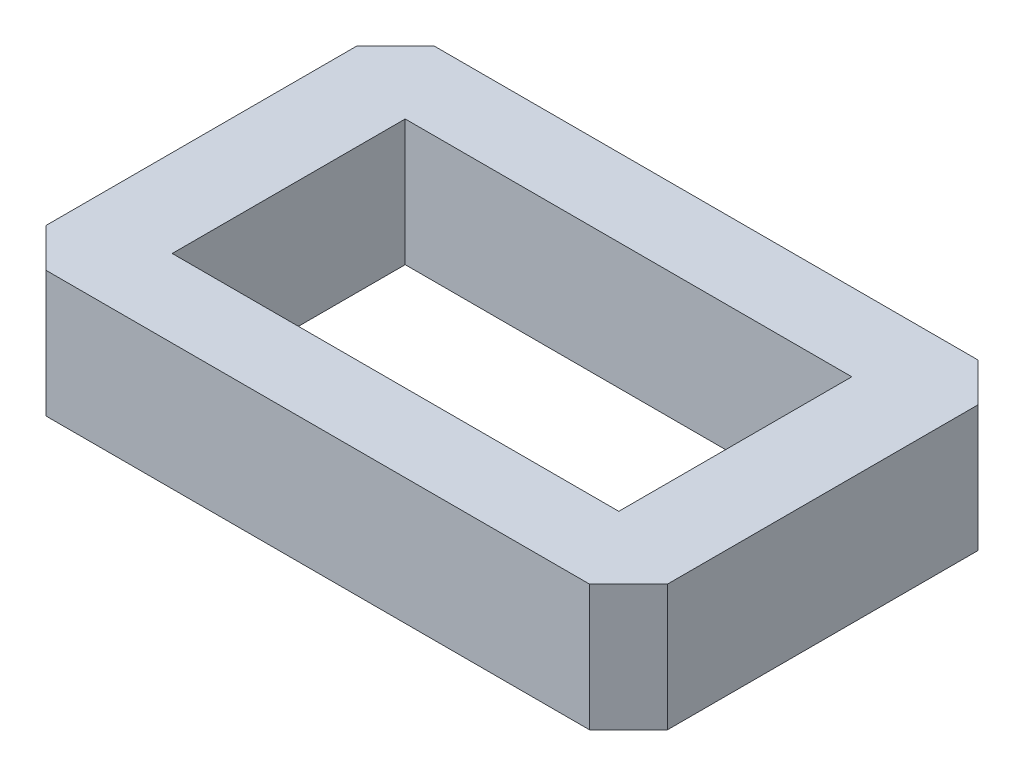
SolidWorks part; units mm, degrees
ref_plane "Front Plane" through (0, 0, 0) normal (0, 0, 1) x (1, 0, 0)
ref_plane "Top Plane" through (0, 0, 0) normal (0, 1, 0) x (1, 0, 0)
ref_plane "Right Plane" through (0, 0, 0) normal (1, 0, 0) x (0, 0, -1)
sketch "Sketch2" plane through (0, 0, 0) normal (0, 1, 0) x (1, 0, 0)
  line L1 (0, 0) -> (32, 0)
  line L2 (0, 0) -> (0, 20)
  line L3 (0, 20) -> (32, 20)
  line L4 (32, 0) -> (32, 20)
  dimension "D1" = 20
  dimension "D2" = 32
extrude "Boss-Extrude1" add sketch "Sketch2" along normal blind 6.5
sketch "Sketch3" plane through (0, 6.5, 0) normal (0, 1, 0) x (1, 0, 0)
  line L0 (16, 20) -> (16, 0) construction
  line L1 (32, 20) -> (0, 20) construction
  line L2 (-3.575, 0) -> (3.575, 0) construction
  line L4 (4.5, 4) -> (27.5, 4)
  line L5 (4.5, 4) -> (4.5, 16)
  line L6 (4.5, 16) -> (27.5, 16)
  line L7 (27.5, 4) -> (27.5, 16)
  line L8 (4.5, 4) -> (27.5, 16) construction
  line L9 (4.5, 16) -> (27.5, 4) construction
  point P6 (16, 10)
  dimension "D1" = 12
  dimension "D2" = 23
extrude "Cut-Extrude1" cut sketch "Sketch3" against normal through all
chamfer "Chamfer1" distance 2 angle 45 4 edges at (0, 3.25, -20) (32, 3.25, -20) (32, 3.25, 0) (0, 3.25, 0)
